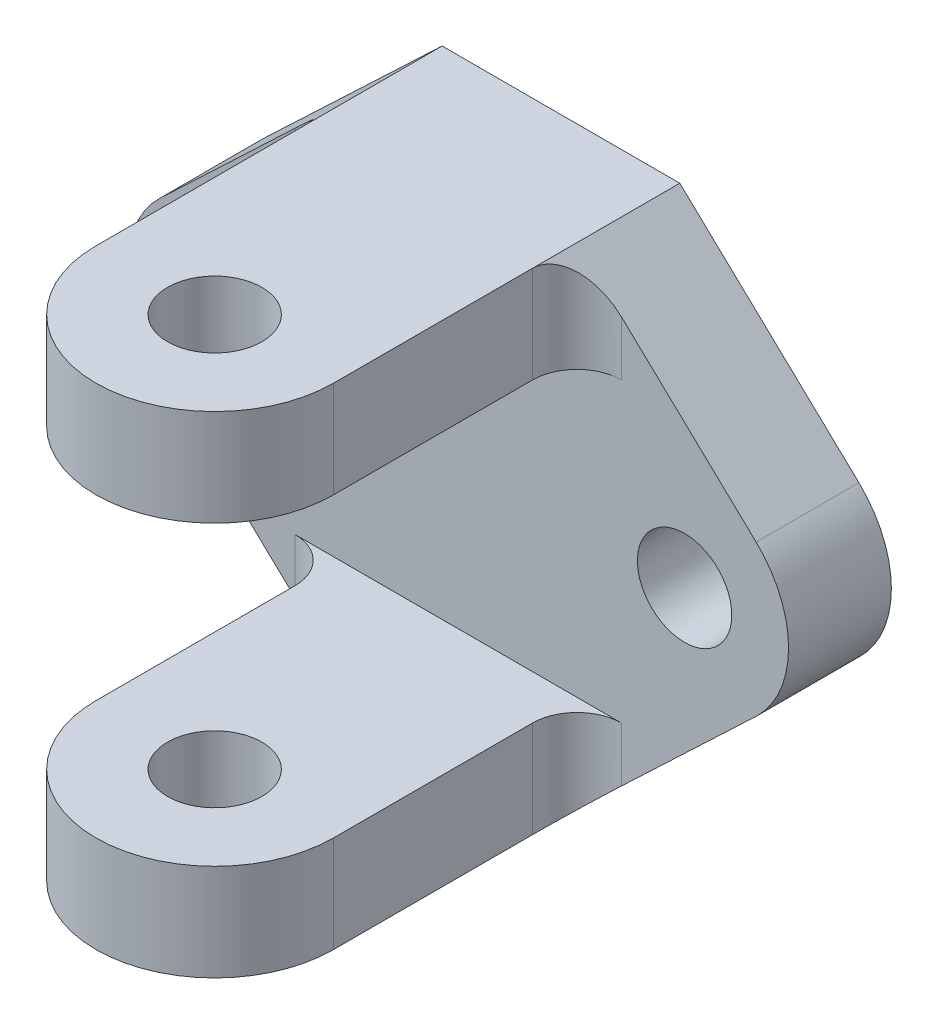
SolidWorks part; units mm, degrees
material "7075-T6 (SN)"
ref_plane "Front Plane" through (0, 0, 0) normal (0, 0, 1) x (1, 0, 0)
ref_plane "Top Plane" through (0, 0, 0) normal (0, 1, 0) x (1, 0, 0)
ref_plane "Right Plane" through (0, 0, 0) normal (1, 0, 0) x (0, 0, -1)
sketch "Sketch1" plane through (0, 0, 0) normal (0, 0, 1) x (1, 0, 0)
  line L0 (15.24, 0) -> (-15.24, 0) construction
  line L1 (-23.24, -16.51) -> (23.24, -16.51)
  line L2 (-23.24, -16.51) -> (-23.24, 16.51)
  line L3 (-23.24, 16.51) -> (23.24, 16.51)
  line L4 (23.24, -16.51) -> (23.24, 16.51)
  line L5 (-23.24, -16.51) -> (23.24, 16.51) construction
  line L6 (-23.24, 16.51) -> (23.24, -16.51) construction
  circle A0 centre (15.24, 0) radius 3.175
  circle A1 centre (-15.24, 0) radius 3.175
  point P0 (0, 0)
  dimension "D1" = 6.35
  dimension "D2" = 30.48
  dimension "D3" = 8
  dimension "D4" = 16.51
extrude "Boss-Extrude1" add sketch "Sketch1" along normal blind 9.46 contours L3 L4 L1 L2
sketch "Sketch2" plane through (0, 0, 9.46) normal (0, 0, 1) x (1, 0, 0)
  line L0 (-15.24, 0) -> (15.24, 0) construction
  line L2 (-23.24, 10) -> (23.24, 10)
  line L3 (-23.24, 10) -> (-23.24, 16.51)
  line L4 (-23.24, 16.51) -> (23.24, 16.51)
  line L5 (23.24, 10) -> (23.24, 16.51)
  line L6 (-23.24, 10) -> (23.24, 16.51) construction
  line L7 (-23.24, 16.51) -> (23.24, 10) construction
  line L8 (-23.24, 16.51) -> (-23.24, -16.51) construction
  line L9 (23.24, -10) -> (23.24, -16.51)
  line L10 (-23.24, -10) -> (-23.24, -16.51)
  line L11 (-23.24, -16.51) -> (23.24, -10) construction
  line L12 (-23.24, -10) -> (23.24, -16.51) construction
  line L13 (-23.24, -10) -> (23.24, -10)
  line L14 (-23.24, -16.51) -> (23.24, -16.51)
  circle A0 centre (-15.24, 0) radius 3.175 construction
  circle A1 centre (15.24, 0) radius 3.175 construction
  point P6 (0, 13.255)
  point P21 (0, -13.255)
  dimension "D1" = 20
extrude "Boss-Extrude2" add sketch "Sketch2" along normal blind 35.982
sketch "Sketch3" plane through (0, 0, 0) normal (0, 1, 0) x (1, 0, 0)
  point P0 (0, -25.8481)
  dimension "D1" = 25.8481
ref_point "UBJ Point"
sketch "Sketch4" plane through (0, 0, 0) normal (0, 1, 0) x (1, 0, 0)
  circle A0 centre (0, -25.8481) radius 3.175
  dimension "D1" = 6.35
extrude "Cut-Extrude1" cut sketch "Sketch4" against normal up to surface and the other way up to surface up to face at (0, -16.51, 22.721) other way up to face at (0, 16.51, 22.721)
sketch "Sketch5" plane through (0, 0, 0) normal (0, 1, 0) x (1, 0, 0)
  line L0 (23.24, -9.46) -> (7.424, -31.2394)
  line L1 (-7.424, -31.2394) -> (-23.24, -9.46)
  line L4 (23.24, 0) -> (-23.24, 0)
  line L5 (-23.24, 0) -> (-23.24, -45.442)
  line L6 (-23.24, -45.442) -> (23.24, -45.442)
  line L7 (23.24, -45.442) -> (23.24, 0)
  line L9 (-23.24, -9.46) -> (-23.24, -45.442)
  line L10 (-23.24, -45.442) -> (23.24, -45.442)
  line L11 (23.24, -45.442) -> (23.24, -9.46)
  line L12 (23.24, -9.46) -> (-23.24, -9.46)
  line L13 (23.24, -45.442) -> (23.24, -9.46)
  line L14 (-23.24, -45.442) -> (23.24, -45.442)
  line L15 (-23.24, -9.46) -> (-23.24, -45.442)
  line L17 (23.24, -45.442) -> (23.24, -9.46)
  line L18 (-23.24, -45.442) -> (23.24, -45.442)
  line L19 (-23.24, -9.46) -> (-23.24, -45.442)
  arc A0 (-7.424, -31.2394) -> (7.424, -31.2394) centre (0, -25.8481) ccw
  circle A1 centre (0, -25.8481) radius 3.175 construction
  circle A2 centre (0, -25.8481) radius 3.175 construction
  dimension "D3" = 6
  dimension "D1" = 0
  dimension "D2" = 0
extrude "Cut-Extrude2" [suppressed] cut sketch "Sketch5" against normal up to surface and the other way up to surface contours A0 L1 L9 L10 L11 L0
sketch "Sketch6" plane through (0, 0, 0) normal (0, 1, 0) x (1, 0, 0)
  line L0 (-8, -25.8481) -> (-8, -17.46)
  line L1 (8, -25.8481) -> (8, -17.46)
  line L2 (-16, -9.46) -> (-23.24, -9.46)
  line L3 (-8, -17.46) -> (-8, -9.46)
  line L4 (23.24, -9.46) -> (-23.24, -9.46)
  line L5 (-23.24, -9.46) -> (-23.24, -45.442)
  line L6 (-23.24, -45.442) -> (23.24, -45.442)
  line L7 (23.24, -45.442) -> (23.24, -9.46)
  line L8 (23.24, -9.46) -> (16, -9.46)
  line L9 (-23.24, -9.46) -> (-23.24, -45.442)
  line L10 (-23.24, -45.442) -> (23.24, -45.442)
  line L11 (23.24, -45.442) -> (23.24, -9.46)
  line L12 (-8, -9.46) -> (-16, -9.46)
  line L13 (8, -17.46) -> (8, -9.46)
  line L14 (8, -9.46) -> (16, -9.46)
  arc A0 (-8, -25.8481) -> (8, -25.8481) centre (0, -25.8481) ccw
  circle A1 centre (0, -25.8481) radius 3.175 construction
  arc A2 (-8, -17.46) -> (-16, -9.46) centre (-16, -17.46) ccw construction
  arc A3 (8, -17.46) -> (16, -9.46) centre (16, -17.46) cw construction
  dimension "D2" = 8
  dimension "D3" = 8
  dimension "D1" = 0
extrude "Cut-Extrude3" cut sketch "Sketch6" against normal up to surface and the other way up to surface
fillet "Fillet1" [suppressed] radius 12.7
sketch "Sketch7" plane through (0, 0, 0) normal (0, 0, 1) x (1, 0, 0)
  line L0 (-15.24, 7) -> (-8, 7)
  line L1 (-15.24, -7) -> (-8, -7)
  line L2 (-8, 10) -> (-8, 7)
  line L3 (-8, -10) -> (-8, -7)
  line L4 (0, 10.3988) -> (0, -8.4154) construction
  line L5 (8, -10) -> (8, -7)
  line L6 (8, 10) -> (8, 16.51)
  line L7 (23.24, 16.51) -> (23.24, -16.51)
  line L8 (8, -10) -> (8, -16.51)
  line L9 (8, 10) -> (8, 7)
  line L10 (15.24, 7) -> (8, 7)
  line L11 (15.24, -7) -> (8, -7)
  line L12 (8, 10) -> (-8, 10)
  line L15 (-23.24, 16.51) -> (-23.24, -16.51)
  line L18 (-8, -10) -> (8, -10)
  line L21 (23.24, -16.51) -> (23.24, 16.51)
  line L27 (-23.24, 16.51) -> (-23.24, -16.51)
  line L33 (23.24, -16.51) -> (23.24, 16.51)
  line L36 (-8, 16.51) -> (-8, 10)
  line L37 (-8, -10) -> (-8, -16.51)
  line L48 (-8, 10) -> (-8, 16.51)
  line L49 (-8, -16.51) -> (-8, -10)
  line L52 (-8, 16.51) -> (-23.24, 16.51)
  line L53 (-8, 16.51) -> (-23.24, 16.51)
  line L54 (-23.24, -16.51) -> (-8, -16.51)
  line L55 (-23.24, -16.51) -> (-8, -16.51)
  line L56 (8, -10) -> (8, -16.51)
  line L57 (8, -16.51) -> (23.24, -16.51)
  line L58 (8, -16.51) -> (23.24, -16.51)
  line L59 (23.24, 16.51) -> (8, 16.51)
  line L60 (23.24, 16.51) -> (8, 16.51)
  line L61 (8, 16.51) -> (8, 10)
  arc A0 (-15.24, 7) -> (-15.24, -7) centre (-15.24, 0) ccw
  circle A1 centre (-15.24, 0) radius 3.175 construction
  arc A2 (15.24, 7) -> (15.24, -7) centre (15.24, 0) cw
  dimension "D2" = 7
  dimension "D1" = 0
extrude "Cut-Extrude4" cut sketch "Sketch7" along normal up to surface (9.46 mm away)
fillet "Fillet2" [suppressed] radius 5
sketch "Sketch8" plane through (0, 0, 0) normal (0, 0, 1) x (1, 0, 0)
  line L0 (15.24, 7) -> (8, 7) construction
  line L1 (8, 16.51) -> (8, 7) construction
  line L2 (15.24, 7) -> (8, 7)
  line L3 (8, 16.51) -> (8, 7)
  line L4 (6.7586, 0) -> (-5.803, 0) construction
  line L5 (0, 7.1591) -> (0, -7.1591) construction
  line L6 (8, 16.51) -> (20.0561, 5.0799)
  line L7 (-8, 16.51) -> (-8, 7)
  line L8 (-15.24, 7) -> (-8, 7)
  line L9 (-8, 16.51) -> (-20.0561, 5.0799)
  line L10 (-8, -16.51) -> (-20.0561, -5.0799)
  line L11 (-15.24, -7) -> (-8, -7)
  line L12 (-8, -16.51) -> (-8, -7)
  line L13 (8, -16.51) -> (8, -7)
  line L14 (15.24, -7) -> (8, -7)
  line L15 (8, -16.51) -> (20.0561, -5.0799)
  arc A0 (15.24, -7) -> (15.24, 7) centre (15.24, 0) ccw construction
  arc A1 (20.0561, 5.0799) -> (15.24, 7) centre (15.24, 0) ccw
  arc A2 (-20.0561, 5.0799) -> (-15.24, 7) centre (-15.24, 0) cw
  arc A3 (-20.0561, -5.0799) -> (-15.24, -7) centre (-15.24, 0) ccw
  arc A4 (20.0561, -5.0799) -> (15.24, -7) centre (15.24, 0) cw
extrude "Boss-Extrude3" add sketch "Sketch8" along normal up to surface (9.46 mm away) contours L15 A4 L14 L13 | A3 L10 L12 L11 | L6 A1 L2 L3 | L9 A2 L8 L7 up to face at (0, 0, 9.46)
fillet "Fillet3" radius 3 4 edges at (8, 13.255, 9.46) (-8, 13.255, 9.46) (-8, -13.255, 9.46) (8, -13.255, 9.46)
sketch "Sketch10" plane through (0, 0, 0) normal (0, 0, 1) x (1, 0, 0)
  line L5 (-8, 16.51) -> (-20.0561, 5.0799)
  line L6 (-8, 16.51) -> (-20.0561, 5.0799)
  line L7 (8, 16.51) -> (-8, 16.51)
  line L8 (20.0561, 5.0799) -> (8, 16.51)
  line L9 (8, -16.51) -> (20.0561, -5.0799)
  line L10 (-8, -16.51) -> (8, -16.51)
  line L13 (8, 16.51) -> (-8, 16.51)
  line L14 (20.0561, 5.0799) -> (8, 16.51)
  line L15 (8, -16.51) -> (20.0561, -5.0799)
  line L16 (-8, -16.51) -> (8, -16.51)
  line L18 (-20.0561, -5.0799) -> (-8, -16.51)
  line L19 (-20.0561, -5.0799) -> (-8, -16.51)
  arc A2 (-20.0561, 5.0799) -> (-20.0561, -5.0799) centre (-15.24, 0) ccw
  arc A3 (20.0561, -5.0799) -> (20.0561, 5.0799) centre (15.24, 0) ccw
  arc A5 (20.0561, -5.0799) -> (20.0561, 5.0799) centre (15.24, 0) ccw
  arc A6 (-20.0561, 5.0799) -> (-20.0561, -5.0799) centre (-15.24, 0) ccw
  dimension "D1" = 0
extrude "Cut-Extrude5" cut sketch "Sketch10" along normal blind 2.54
